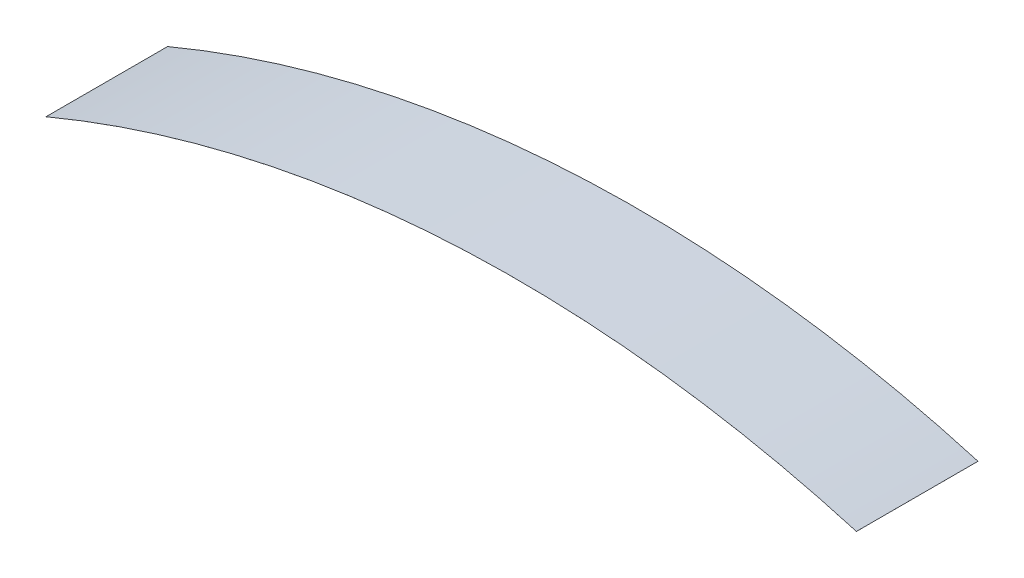
SolidWorks part; units mm, degrees
ref_plane "Front Plane" through (0, 0, 0) normal (0, 0, 1) x (1, 0, 0)
ref_plane "Top Plane" through (0, 0, 0) normal (0, 1, 0) x (1, 0, 0)
ref_plane "Right Plane" through (0, 0, 0) normal (1, 0, 0) x (0, 0, -1)
sketch "Sketch1" plane through (0, 0, 0) normal (0, 0, 1) x (1, 0, 0)
  arc A0 (41.9768, 144.0068) -> (-58.0232, 138.3232) centre (0, 0) ccw
  dimension "D1" = 300
  dimension "D2" = 100
extrude "Extrude-Thin1" add sketch "Sketch1" along normal blind 15 thin
